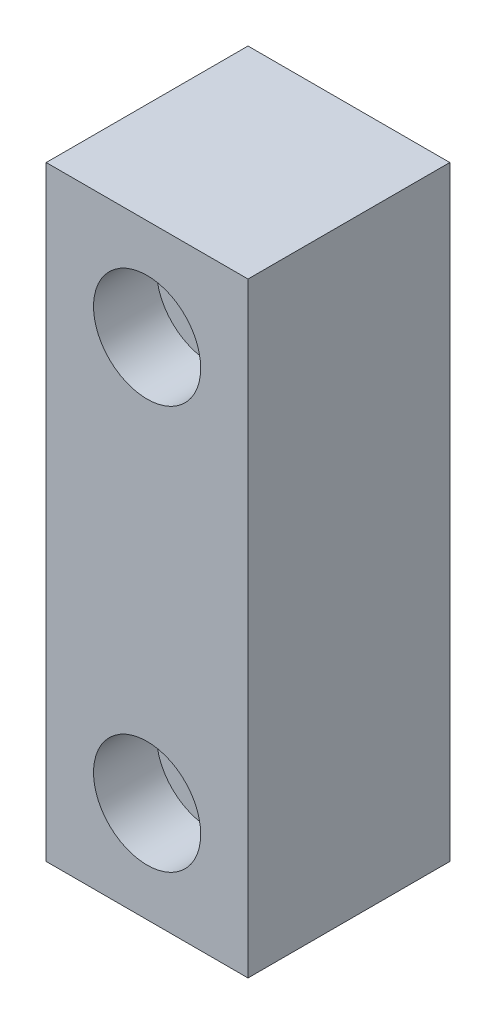
SolidWorks part; units mm, degrees
ref_plane "Front Plane" through (0, 0, 0) normal (1, 0, 0) x (0, 1, 0)
ref_plane "Top Plane" through (0, 0, 0) normal (0, 0, 1) x (0, 1, 0)
ref_plane "Right Plane" through (0, 0, 0) normal (0, 1, 0) x (-1, 0, 0)
sketch "Sketch1" plane through (0, 0, 0) normal (0, 0, 1) x (0, 1, 0)
  line L1 (-38.1, -12.7) -> (38.1, -12.7)
  line L2 (-38.1, -12.7) -> (-38.1, 12.7)
  line L3 (-38.1, 12.7) -> (38.1, 12.7)
  line L4 (38.1, -12.7) -> (38.1, 12.7)
  line L5 (-38.1, -12.7) -> (38.1, 12.7) construction
  line L6 (-38.1, 12.7) -> (38.1, -12.7) construction
  point P0 (0, 0)
extrude "Boss-Extrude1" add sketch "Sketch1" along normal mid plane 25.4
sketch "Sketch2" plane through (0, 0, 0) normal (0, 0, 1) x (0, 1, 0)
  circle A0 centre (-25.4, 0) radius 4.3688
extrude "Cut-Extrude2" cut sketch "Sketch2" against normal blind 76.2 from offset 12.7
sketch "Sketch3" plane through (0, 0, 0) normal (0, 0, 1) x (0, 1, 0)
  circle A0 centre (-25.4, 0) radius 6.7437
extrude "Cut-Extrude4" cut sketch "Sketch3" against normal blind 7.9248 from offset 12.7
sketch "Sketch4" plane through (0, 0, 0) normal (0, 0, 1) x (0, 1, 0)
  circle A0 centre (25.4, 0) radius 4.3688
extrude "Cut-Extrude6" cut sketch "Sketch4" against normal blind 76.2 from offset 12.7
sketch "Sketch5" plane through (0, 0, 0) normal (0, 0, 1) x (0, 1, 0)
  circle A0 centre (25.4, 0) radius 6.7437
extrude "Cut-Extrude8" cut sketch "Sketch5" against normal blind 7.9248 from offset 12.7
